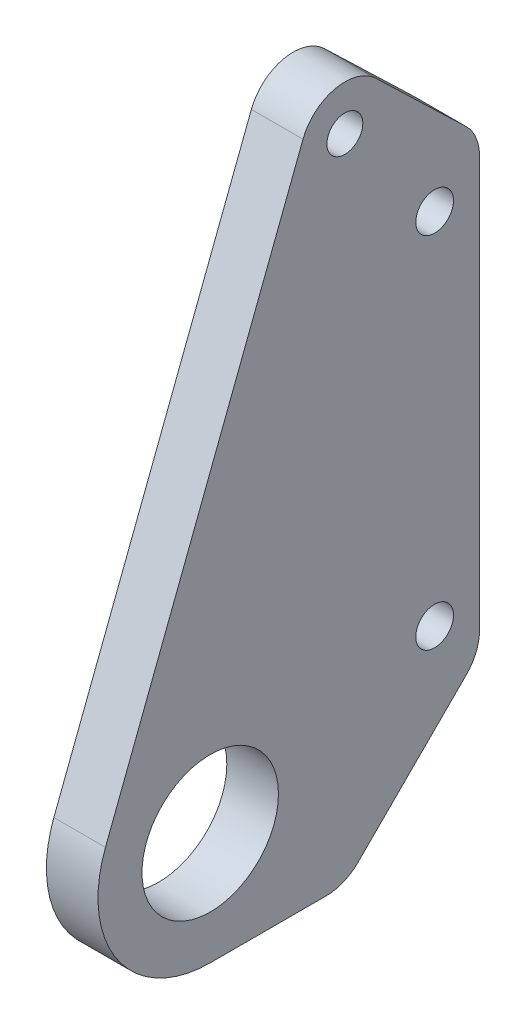
SolidWorks part; units mm, degrees
material "MC901"
ref_plane "正面" through (0, 0, 0) normal (0, 0, 1) x (1, 0, 0)
ref_plane "平面" through (0, 0, 0) normal (0, 1, 0) x (1, 0, 0)
ref_plane "右側面" through (0, 0, 0) normal (1, 0, 0) x (0, 0, -1)
sketch "ｽｹｯﾁ1" plane through (0, 0, 0) normal (1, 0, 0) x (0, 0, -1)
  line L0 (0, 15) -> (0, 65)
  line L6 (-19.6679, 74.292) -> (-41.6696, 16.9799)
  line L7 (-30, 0) -> (-15, 0)
  line L12 (-5, 60) -> (-5, 0) construction
  line L19 (-12.6021, 76.8875) -> (0, 70) construction
  line L20 (0, 65) -> (-23.235, 65) construction
  line L21 (0, 65) -> (-11.5323, 76.1021)
  line L22 (0, 65) -> (0, 70) construction
  line L23 (0, 15) -> (-42.2474, 15) construction
  line L24 (0, 15) -> (-15, 0)
  line L25 (-5, 0) -> (0, 0) construction
  line L26 (-15, 0) -> (-5, 0) construction
  line L27 (0, 0) -> (0, 15) construction
  arc A5 (-41.6696, 16.9799) -> (-30, 0) centre (-30, 12.5) ccw
  circle A6 centre (-5, 20) radius 2.1
  circle A7 centre (-5, 60) radius 2.1
  circle A8 centre (-30, 12.5) radius 7.6
  arc A9 (-12.6021, 76.8875) -> (-19.6679, 74.292) centre (-15, 72.5) ccw
  circle A12 centre (-15, 72.5) radius 2
  circle A13 centre (-15, 72.5) radius 5
  point P19 (0, 70)
  dimension "D4" = 20
  dimension "D7" = 12.5
  dimension "D9" = 15
  dimension "D13" = 5
  dimension "D3" = 4.2
  dimension "D5" = 60
  dimension "D8" = 15.2
  dimension "D11" = 40
  dimension "D12" = 5
  dimension "D15" = 5
  dimension "D16" = 4
  dimension "D6" = 30
  dimension "D2" = 70
  dimension "D10" = 5
  dimension "D14" = 45
extrude "ﾎﾞｽ - 押し出し1" add sketch "ｽｹｯﾁ1" along normal blind 5.75
sketch "ｽｹｯﾁ2" plane through (5.75, 0, 0) normal (1, 0, 0) x (0, 0, -1)
  line L0 (-10.2884, 63.8464) -> (-21.0402, 35.8393) construction
  line L1 (-5.6205, 62.0544) -> (-16.3723, 34.0473)
  line L2 (-14.9563, 65.6384) -> (-25.708, 37.6312)
  line L3 (0.4634, 91.8535) -> (-30, 12.5) construction
  line L4 (-19.6679, 74.292) -> (-41.6696, 16.9799) construction
  arc A0 (-5.6205, 62.0544) -> (-14.9563, 65.6384) centre (-10.2884, 63.8464) ccw
  arc A1 (-25.708, 37.6312) -> (-16.3723, 34.0473) centre (-21.0402, 35.8393) ccw
  point P2 (-15.6643, 49.8428)
  dimension "D1" = 30
  dimension "D2" = 30
  dimension "D3" = 10
  dimension "D4" = 85
extrude "body cut" [suppressed] cut sketch "ｽｹｯﾁ2" against normal up to surface (5.75 mm away)
fillet "ﾌｨﾚｯﾄ1" radius 5 3 edges at (2.875, 0, 15) (2.875, 15, 0) (2.875, 65, 0)
